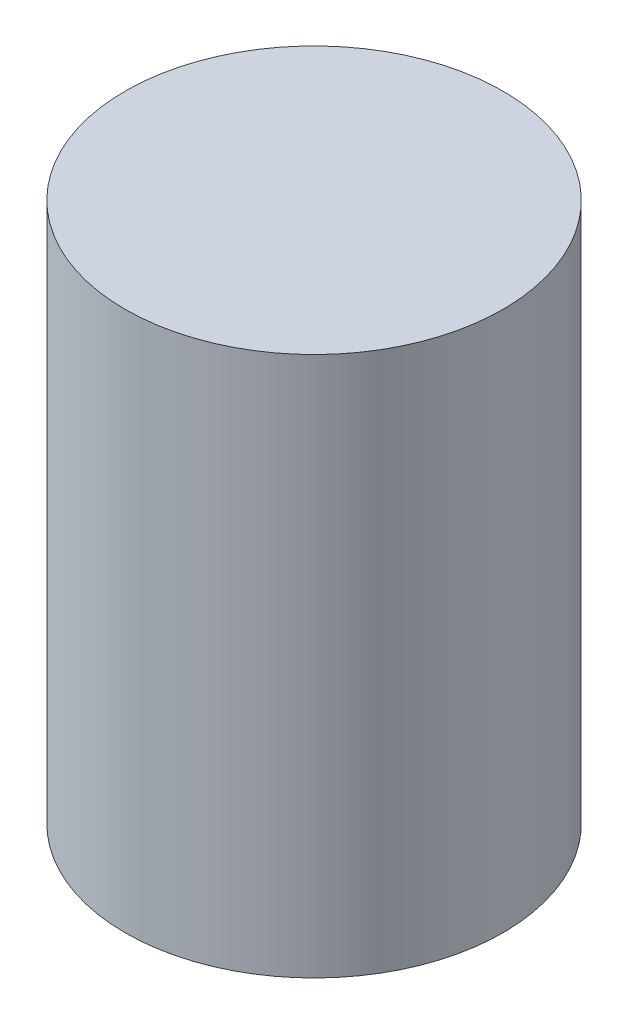
SolidWorks part; units mm, degrees
ref_plane "Front Plane" through (0, 0, 0) normal (0, 0, 1) x (1, 0, 0)
ref_plane "Top Plane" through (0, 0, 0) normal (0, 1, 0) x (1, 0, 0)
ref_plane "Right Plane" through (0, 0, 0) normal (1, 0, 0) x (0, 0, -1)
sketch "Sketch1" plane through (0, 0, 0) normal (0, 1, 0) x (1, 0, 0)
  circle A0 centre (0, 0) radius 10.5
  dimension "D1" = 21
extrude "Boss-Extrude1" add sketch "Sketch1" along normal blind 30
